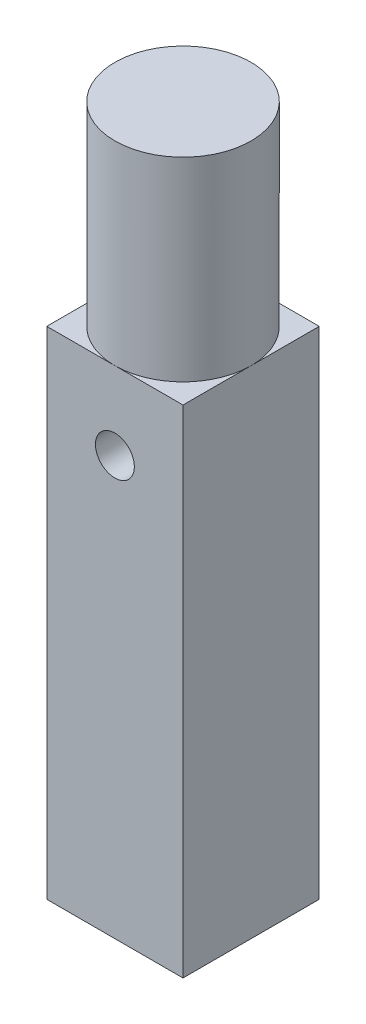
SolidWorks part; units mm, degrees
ref_plane "Front Plane" through (0, 0, 0) normal (0, 0, 1) x (1, 0, 0)
ref_plane "Top Plane" through (0, 0, 0) normal (0, 1, 0) x (1, 0, 0)
ref_plane "Right Plane" through (0, 0, 0) normal (1, 0, 0) x (0, 0, -1)
sketch "Sketch1" plane through (0, 0, 0) normal (0, 1, 0) x (1, 0, 0)
  line L1 (-44.45, 44.45) -> (44.45, 44.45)
  line L2 (-44.45, 44.45) -> (-44.45, -44.45)
  line L3 (-44.45, -44.45) -> (44.45, -44.45)
  line L4 (44.45, 44.45) -> (44.45, -44.45)
  line L5 (-44.45, 44.45) -> (44.45, -44.45) construction
  line L6 (-44.45, -44.45) -> (44.45, 44.45) construction
  point P0 (0, 0)
  dimension "D1" = 88.9
  dimension "D2" = 88.9
extrude "Boss-Extrude1" add sketch "Sketch1" along normal blind 450.85
sketch "Sketch2" plane through (0, 450.85, 0) normal (0, 1, 0) x (1, 0, 0)
  circle A0 centre (0, 0) radius 44.45
  line M2 (44.45, -44.45) -> (44.45, 44.45)
  line M3 (44.45, 44.45) -> (-44.45, 44.45)
  line M4 (-44.45, 44.45) -> (-44.45, -44.45)
  line M5 (-44.45, -44.45) -> (44.45, -44.45)
extrude "Cut-Extrude1" cut sketch "Sketch2" against normal blind 127 contours A0 M4 M5 | A0 M3 M4 | A0 M2 M3 | A0 M5 M2
sketch "Sketch3" plane through (0, 0, 0) normal (0, 0, 1) x (1, 0, 0)
  line L0 (0, 273.05) -> (0, 450.85) construction
  line L1 (44.45, 450.85) -> (-44.45, 450.85) construction
  circle A0 centre (0, 273.05) radius 12.7
  dimension "D1" = 25.4
  dimension "D2" = 177.8
extrude "Cut-Extrude2" cut sketch "Sketch3" against normal through all both and the other way through all contours A0
